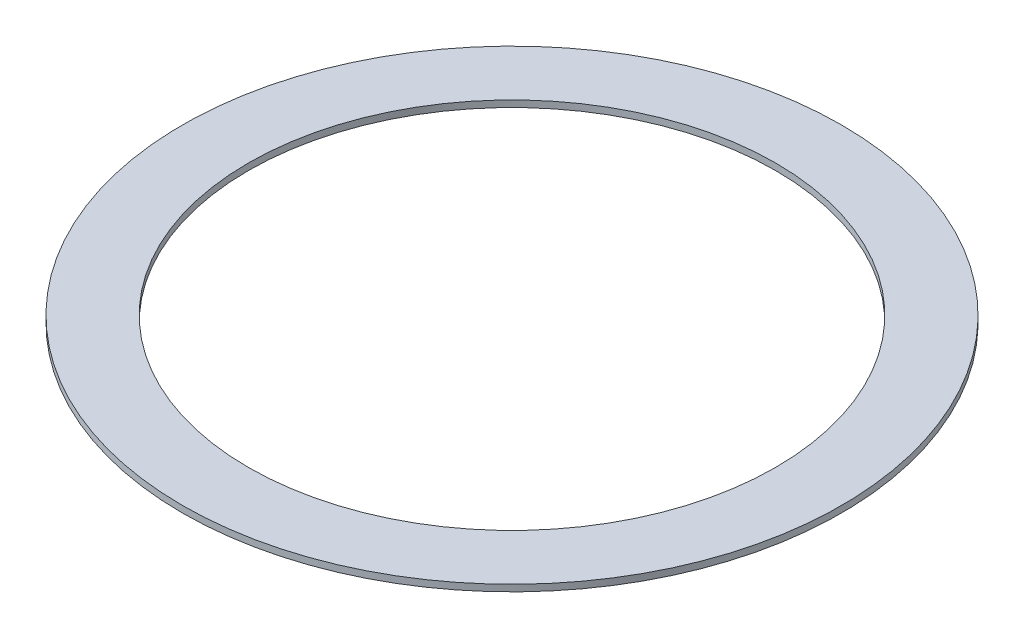
SolidWorks part; units mm, degrees
ref_plane "前视基准面" through (0, 0, 0) normal (0, 0, 1) x (1, 0, 0)
ref_plane "上视基准面" through (0, 0, 0) normal (0, 1, 0) x (1, 0, 0)
ref_plane "右视基准面" through (0, 0, 0) normal (1, 0, 0) x (0, 0, -1)
sketch "草图1" plane through (0, 0, 0) normal (0, 1, 0) x (1, 0, 0)
  circle A0 centre (0, 0) radius 100
  circle A1 centre (0, 0) radius 80
extrude "凸台-拉伸1" add sketch "草图1" along normal blind 2
